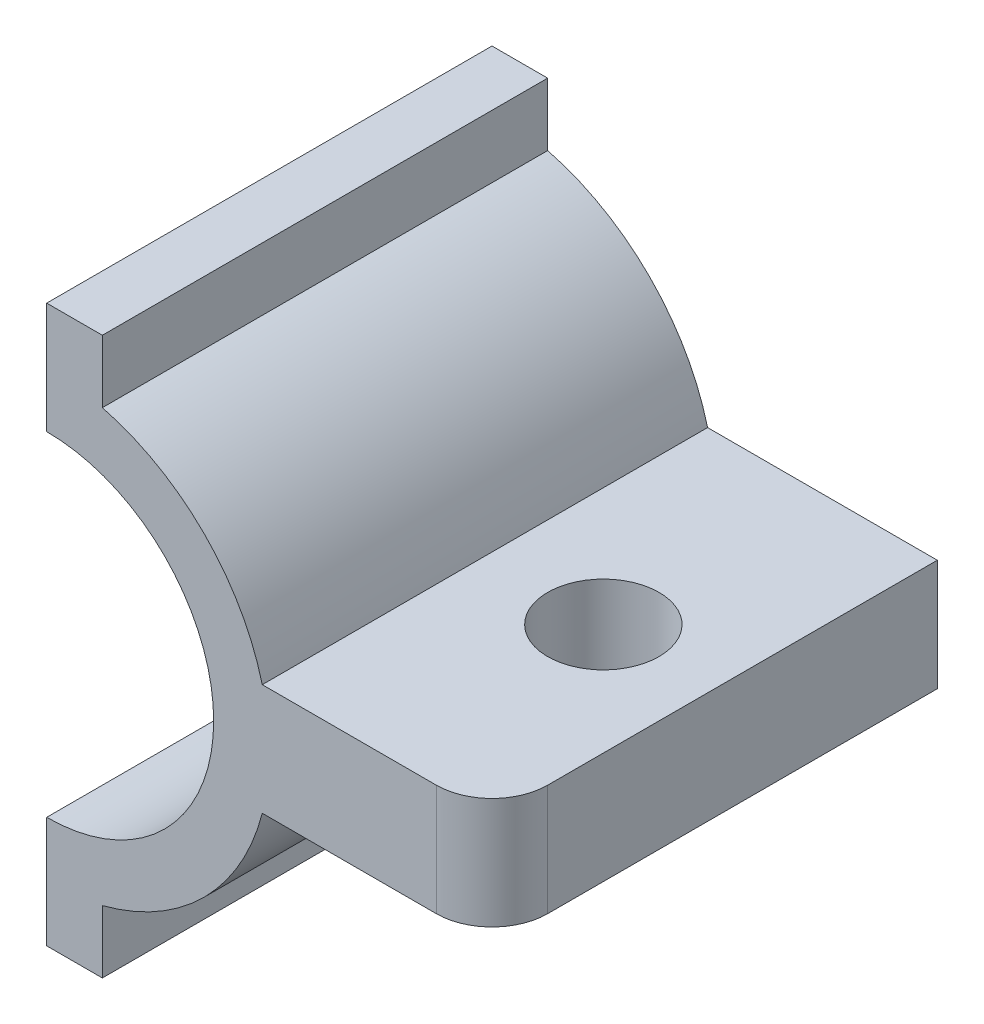
SolidWorks part; units mm, degrees
ref_plane "前基準面" through (0, 0, 0) normal (0, 0, 1) x (1, 0, 0)
ref_plane "上基準面" through (0, 0, 0) normal (0, 1, 0) x (1, 0, 0)
ref_plane "右基準面" through (0, 0, 0) normal (1, 0, 0) x (0, 0, -1)
sketch "草圖1" plane through (0, 0, 0) normal (0, 0, 1) x (1, 0, 0)
  line L0 (-49.7165, 0) -> (77.8223, 0) construction
  line L2 (0, -30) -> (0, -50)
  line L3 (0, -50) -> (10, -50)
  line L4 (10, -38.7298) -> (10, -50)
  line L5 (38.7298, 10) -> (80, 10)
  line L6 (0, 30) -> (0, 50)
  line L7 (0, 50) -> (10, 50)
  line L8 (10, 38.7298) -> (10, 50)
  line L10 (38.7298, -10) -> (80, -10)
  line L11 (80, 10) -> (80, -10)
  arc A0 (0, -30) -> (0, 30) centre (0, 0) ccw
  arc A1 (10, -38.7298) -> (38.7298, -10) centre (0, 0) ccw
  arc A2 (38.7298, 10) -> (10, 38.7298) centre (0, 0) ccw
  point P17 (0, 0)
  dimension "D1" = 60
  dimension "D2" = 80
  dimension "D3" = 10
  dimension "D4" = 10
  dimension "D5" = 100
  dimension "D6" = 20
  dimension "D7" = 80
extrude "填料-伸長1" add sketch "草圖1" along normal blind 80
sketch "草圖2" plane through (0, -10, 0) normal (0, -1, 0) x (1, 0, 0)
  line L0 (38.7298, 0) -> (80, 0) construction
  line L1 (80, 80) -> (80, 0) construction
  circle A0 centre (60, 40) radius 10
  dimension "D3" = 20
  dimension "D1" = 40
  dimension "D2" = 20
extrude "除料-伸長1" cut sketch "草圖2" against normal through all
fillet "圓角1" radius 10 1 edges at (80, 0, 80)
